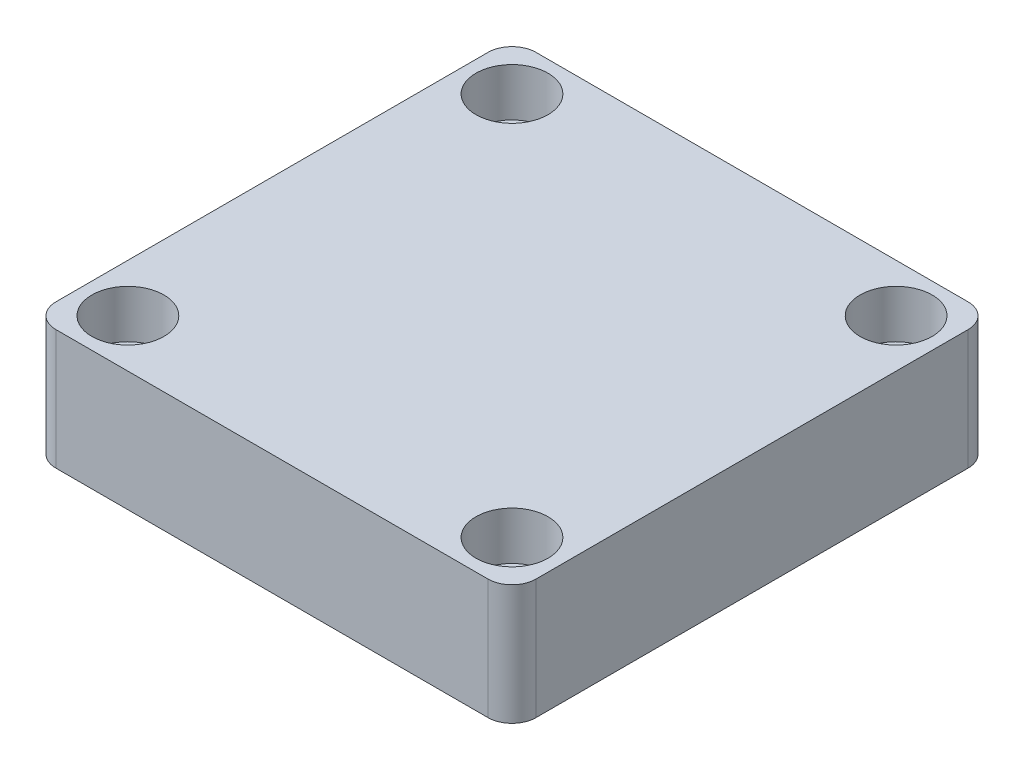
SolidWorks part; units mm, degrees
ref_plane "Спереди" through (0, 0, 0) normal (0, 0, 1) x (1, 0, 0)
ref_plane "Сверху" through (0, 0, 0) normal (0, 1, 0) x (1, 0, 0)
ref_plane "Справа" through (0, 0, 0) normal (1, 0, 0) x (0, 0, -1)
sketch "Эскиз1" plane through (0, 0, 0) normal (0, 1, 0) x (1, 0, 0)
  line L1 (-19.7163, 11.844) -> (20.2837, 11.844)
  line L2 (-19.7163, 11.844) -> (-19.7163, -28.156)
  line L3 (-19.7163, -28.156) -> (20.2837, -28.156)
  line L4 (20.2837, 11.844) -> (20.2837, -28.156)
  circle A0 centre (-15.7163, 7.844) radius 1.5
  circle A1 centre (16.2837, 7.844) radius 1.5
  circle A2 centre (16.2837, -24.156) radius 1.5
  circle A3 centre (-15.7163, -24.156) radius 1.5
  dimension "D3" = 4
  dimension "D5" = 3
  dimension "D6" = 2
  dimension "D1" = 40
  dimension "D2" = 40
  dimension "D4" = 4
  dimension "D7" = 2
extrude "Бобышка-Вытянуть1" add sketch "Эскиз1" along normal blind 10
fillet "Скругление1" radius 2 4 edges at (-19.7163, 5, 28.156) (20.2837, 5, 28.156) (20.2837, 5, -11.844) (-19.7163, 5, -11.844)
sketch "Эскиз2" plane through (0, 10, 0) normal (0, 1, 0) x (1, 0, 0)
  circle A0 centre (-15.7163, 7.844) radius 3
  circle A1 centre (16.2837, 7.844) radius 3
  circle A2 centre (16.2837, -24.156) radius 3
  circle A3 centre (-15.7163, -24.156) radius 3
  dimension "D1" = 2
  dimension "D2" = 2
extrude "Вырез-Вытянуть1" cut sketch "Эскиз2" against normal blind 4
